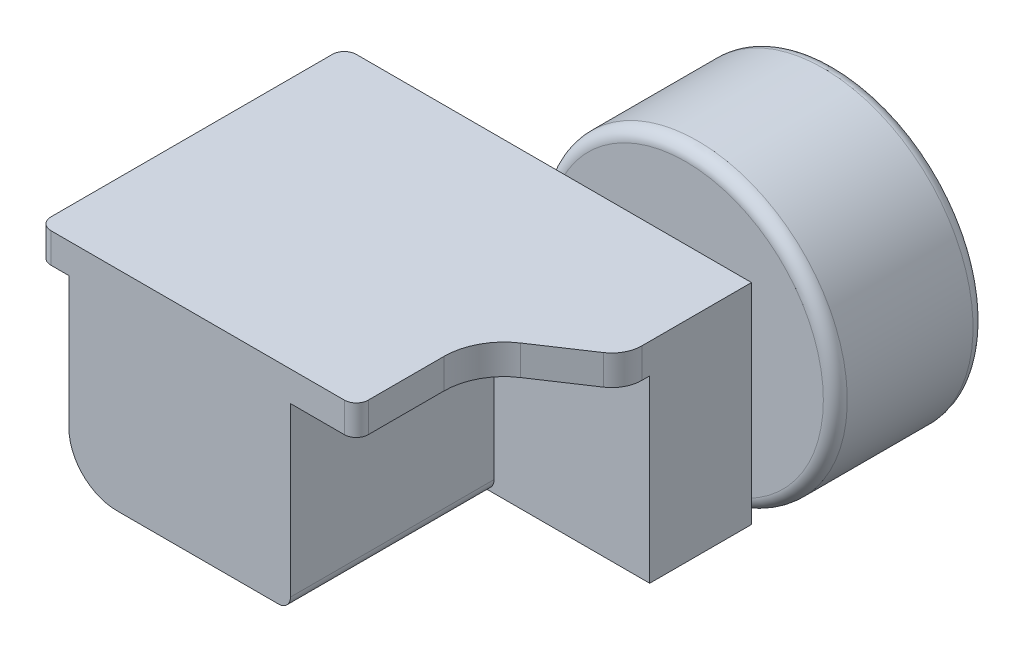
SolidWorks part; units mm, degrees
ref_plane "Plan de face" through (0, 0, 0) normal (0, 0, 1) x (1, 0, 0)
ref_plane "Plan de dessus" through (0, 0, 0) normal (0, 1, 0) x (1, 0, 0)
ref_plane "Plan de droite" through (0, 0, 0) normal (1, 0, 0) x (0, 0, -1)
sketch "Esquisse1" plane through (0, 0, 0) normal (0, 0, 1) x (1, 0, 0)
  line L1 (0, 0) -> (68, 0)
  line L2 (0, 0) -> (0, 35)
  line L3 (0, 35) -> (68, 35)
  line L4 (68, 0) -> (68, 35)
  dimension "D1" = 68
  dimension "D2" = 35
extrude "Boss.-Extru.1" add sketch "Esquisse1" along normal blind 51
sketch "Esquisse2" plane through (0, 0, 0) normal (0, 0, -1) x (-1, 0, 0)
  line L0 (-68, 35) -> (0, 35) construction
  line L2 (-68, 0) -> (-68, 35) construction
  circle A0 centre (-50, 17) radius 6
  dimension "D1" = 18
  dimension "D2" = 18
extrude "Boss.-Extru.2" add sketch "Esquisse2" along normal blind 7
sketch "Esquisse3" plane through (0, 0, -7) normal (0, 0, -1) x (-1, 0, 0)
  circle A0 centre (-50, 17) radius 25
  point P0 (-50, 17)
extrude "Boss.-Extru.3" add sketch "Esquisse3" along normal blind 25
sketch "Esquisse4" plane through (0, 0, -32) normal (0, 0, -1) x (-1, 0, 0)
  circle A0 centre (-50, 17) radius 18
  circle A1 centre (-50, 17) radius 6
  point P0 (-50, 17)
extrude "Enlèv. mat.-Extru.1" cut sketch "Esquisse4" against normal blind 7
fillet "Congé1" radius 2 6 edges at (44, 17, -25) (32, 17, -25) (25, 17, -32) (32, 17, -32) (25, 17, -7) (44, 17, -32)
sketch "Esquisse6" plane through (0, 0, 0) normal (0, -1, 0) x (-1, 0, 0)
  line L0 (-53, -51) -> (-53, -36.3518)
  line L1 (0, -51) -> (-68, -51) construction
  line L2 (-57.453, -28.0313) -> (-68, -21)
  line L3 (-68, -51) -> (-68, 0) construction
  line L4 (-68, -21) -> (-68, -51)
  line L5 (-68, -51) -> (-53, -51)
  arc A0 (-53, -36.3518) -> (-57.453, -28.0313) centre (-63, -36.3518) ccw
  point P11 (-53, -31)
  dimension "D4" = 10
  dimension "D1" = 15
  dimension "D2" = 30
  dimension "D3" = 20
extrude "Enlèv. mat.-Extru.2" cut sketch "Esquisse6" against normal through all
fillet "Congé2" radius 5 1 edges at (68, 17.5, 21)
sketch "Esquisse7" plane through (0, 0, 0) normal (0, -1, 0) x (1, 0, 0)
  line L1 (0, 51) -> (68, 51) construction
  line L2 (68, 51) -> (68, 0) construction
  line L4 (68, 51) -> (42, 51)
  line L5 (68, 51) -> (68, 17)
  line L6 (68, 17) -> (42, 17)
  line L7 (42, 51) -> (42, 17)
  dimension "D1" = 34
  dimension "D2" = 26
extrude "Enlèv. mat.-Extru.3" cut sketch "Esquisse7" against normal blind 30
sketch "Esquisse8" plane through (0, 0, 0) normal (0, -1, 0) x (1, 0, 0)
  line L0 (0, 0) -> (13, 0)
  line L1 (0, 0) -> (68, 0) construction
  line L2 (13, 0) -> (13, 14)
  line L3 (13, 14) -> (5, 14)
  line L4 (5, 14) -> (5, 51)
  line L5 (0, 51) -> (42, 51) construction
  line L6 (5, 51) -> (0, 51)
  line L7 (0, 51) -> (0, 0)
  dimension "D1" = 13
  dimension "D2" = 14
  dimension "D3" = 5
extrude "Enlèv. mat.-Extru.4" cut sketch "Esquisse8" against normal blind 30
fillet "Congé3" radius 8 1 edges at (5, 0, 32.5)
fillet "Congé4" radius 2 1 edges at (42, 0, 34)
fillet "Congé5" radius 2 3 edges at (0, 32.5, 51) (53, 32.5, 51) (0, 32.5, 0)
